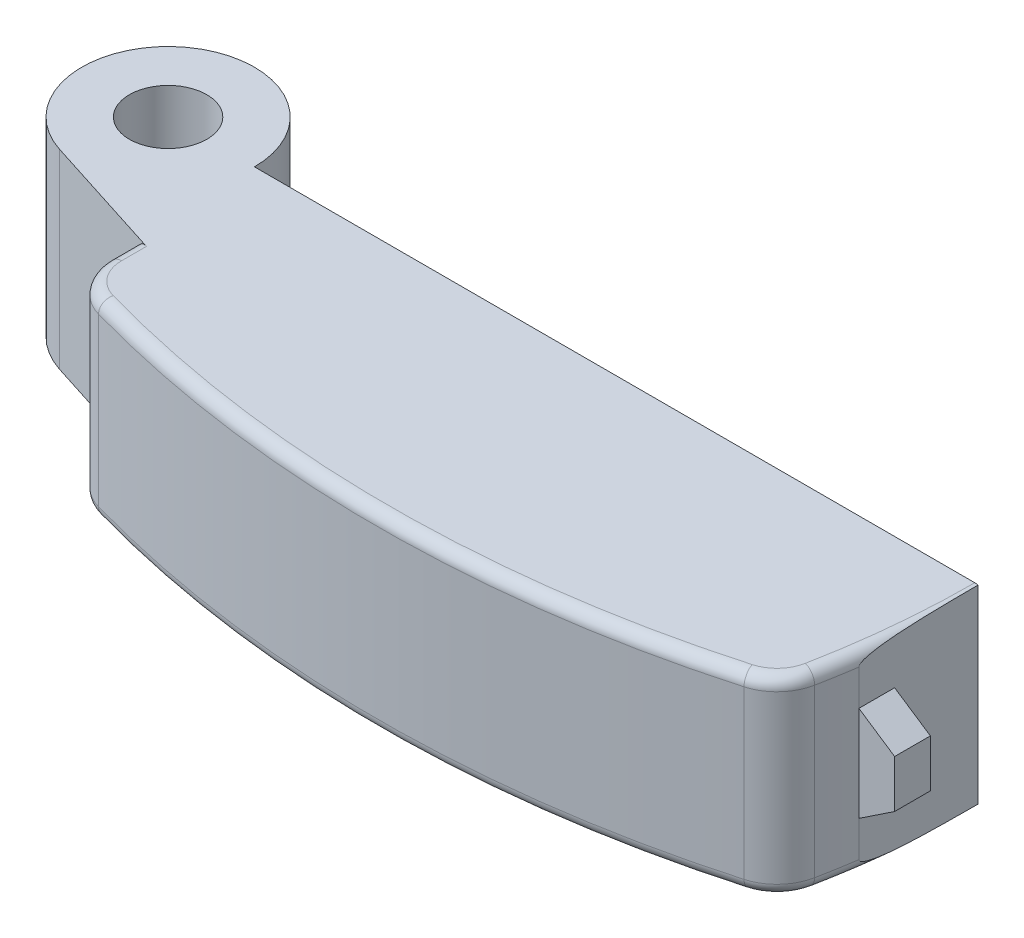
SolidWorks part; units mm, degrees
ref_plane "Front Plane" through (0, 0, 0) normal (0, 0, 1) x (1, 0, 0)
ref_plane "Top Plane" through (0, 0, 0) normal (0, 1, 0) x (1, 0, 0)
ref_plane "Right Plane" through (0, 0, 0) normal (1, 0, 0) x (0, 0, -1)
sketch "Sketch1" plane through (0, 0, 0) normal (0, 1, 0) x (1, 0, 0)
  line L0 (3.625, 0) -> (34, 0)
  line L2 (3.75, -6.2039) -> (3.75, -5)
  line L3 (-1.1009, -3.4538) -> (3.75, -5)
  line L4 (5.3249, -10) -> (19.1895, -10) construction
  line L5 (5.208, -8.129) -> (32.3075, -8.129) construction
  line L6 (33.9098, -5.5789) -> (34.7531, -4.9782) construction
  line L7 (34, 0) -> (34, -5)
  arc A1 (33.7284, -6.5872) -> (32.3075, -8.129) centre (31.7655, -6.2039) cw
  circle A2 centre (0, 0) radius 1.625
  arc A3 (3.625, 0) -> (-1.1009, -3.4538) centre (0, 0) ccw
  arc A5 (3.75, -6.2039) -> (5.208, -8.129) centre (5.75, -6.2039) ccw
  arc A6 (5.208, -8.129) -> (32.3075, -8.129) centre (18.7578, 40) ccw
  arc A7 (34, -5) -> (33.7284, -6.5872) centre (0, 0) cw
  dimension "D1" = 34
  dimension "D3" = 2
  dimension "D2" = 3.25
  dimension "D4" = 2
  dimension "D6" = 50
  dimension "D5" = 10
  dimension "D7" = 3.75
  dimension "D8" = 5
  dimension "D9" = 0.7531
extrude "Boss-Extrude1" add sketch "Sketch1" against normal mid plane 8 contours L0 A1 A6 A5 L2 L3 A3
shell "Shell1" [suppressed] thickness 1.5
ref_plane "Plane1" through (0, 0, 5) normal (0, 0, 1) x (1, 0, 0)
sketch "Sketch3" plane through (0, 0, 5) normal (0, 0, -1) x (-1, 0, 0)
  line L0 (-34, -4) -> (-34, -2) construction
  line L6 (-34, -2) -> (-35.5, -1)
  line L7 (-35.5, -1) -> (-35.5, 1)
  line L8 (-35.5, 1) -> (-34, 2)
  line L9 (-34, 2) -> (-34, 4) construction
  line L11 (-34, 2) -> (-34, -2)
  line L12 (-34, -4) -> (-34, 4) construction
  dimension "D1" = 1.5
  dimension "D2" = 2
  dimension "D3" = 4
extrude "Boss-Extrude2" add sketch "Sketch3" along normal blind 1.5 contours L6 L7 L8 L11
fillet "Fillet1" radius 0.5 10 edges at (3.75, 4, 5.6019) (4.1556, 4, 7.4114) (33.8735, 4, 5.7952) (33.2362, 4, 7.5593) (3.75, -4, 5.6019) (4.1556, -4, 7.4114) (33.8735, -4, 5.7952) (33.2362, -4, 7.5593) (18.7578, 4, 10) (18.7578, -4, 10)
sketch "Sketch4" plane through (0, 0, 0) normal (0, 0, -1) x (-1, 0, 0)
  line L0 (-30, 0) -> (0, 0) construction
  line L1 (-32, 2.5) -> (-28, 2.5)
  line L2 (-32, 2.5) -> (-32, -2.5)
  line L3 (-32, -2.5) -> (-28, -2.5)
  line L4 (-28, 2.5) -> (-28, -2.5)
  line L5 (-32, 2.5) -> (-28, -2.5) construction
  line L6 (-32, -2.5) -> (-28, 2.5) construction
  point P0 (-30, 0)
  dimension "D1" = 4
  dimension "D2" = 5
  dimension "D3" = 30
extrude "Cut-Extrude1" cut sketch "Sketch4" against normal blind 4
